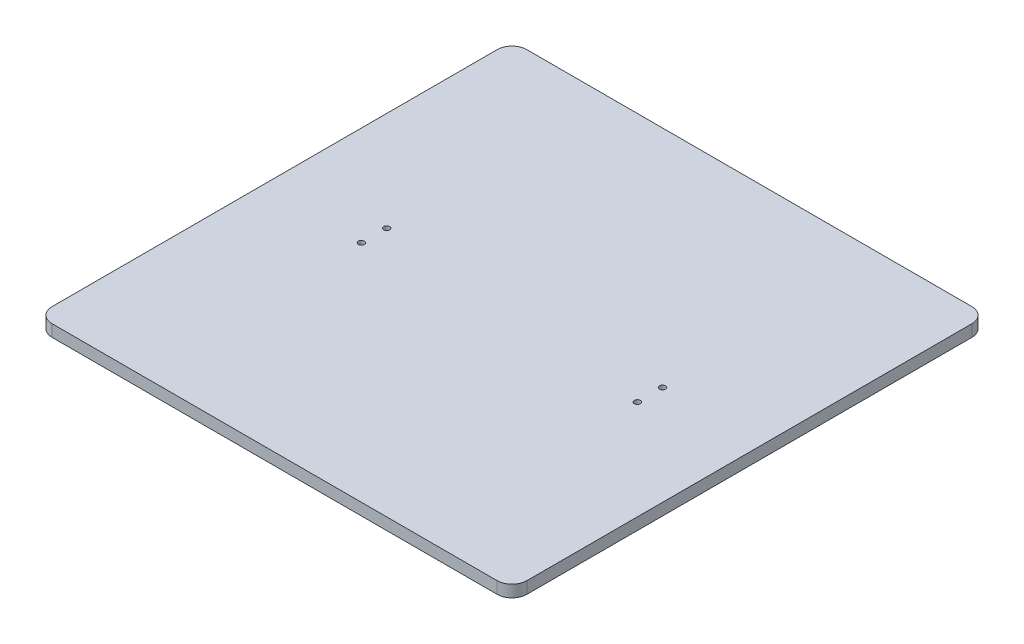
SolidWorks part; units mm, degrees
material "PMMA"
ref_plane "前视基准面" through (0, 0, 0) normal (0, 0, 1) x (1, 0, 0)
ref_plane "上视基准面" through (0, 0, 0) normal (0, 1, 0) x (1, 0, 0)
ref_plane "右视基准面" through (0, 0, 0) normal (1, 0, 0) x (0, 0, -1)
sketch "草图1" plane through (0, 0, 0) normal (0, 1, 0) x (1, 0, 0)
  line L1 (-150, -160) -> (150, -160)
  line L2 (-160, -150) -> (-160, 150)
  line L3 (-150, 160) -> (150, 160)
  line L4 (160, -150) -> (160, 150)
  line L5 (-160, -160) -> (160, 160) construction
  line L6 (-160, 160) -> (160, -160) construction
  arc A0 (160, -150) -> (150, -160) centre (150, -150) cw
  arc A1 (-150, -160) -> (-160, -150) centre (-150, -150) cw
  arc A2 (160, 150) -> (150, 160) centre (150, 150) ccw
  arc A3 (-150, 160) -> (-160, 150) centre (-150, 150) ccw
  point P0 (0, 0)
  dimension "D3" = 10
  dimension "D1" = 320
  dimension "D2" = 320
extrude "凸台-拉伸1" add sketch "草图1" against normal blind 8
sketch "草图2" plane through (0, -8, 0) normal (0, -1, 0) x (1, 0, 0)
  line L0 (-160, 0) -> (160, 0) construction
  line L1 (-160, -150) -> (-160, 150) construction
  line L2 (160, 150) -> (160, -150) construction
  line L3 (0, 160) -> (0, -160) construction
  line L4 (-150, 160) -> (150, 160) construction
  line L5 (150, -160) -> (-150, -160) construction
  circle A0 centre (-93, 8.5) radius 2
  circle A1 centre (93, 8.5) radius 2
  circle A2 centre (93, -8.5) radius 2
  circle A3 centre (-93, -8.5) radius 2
  dimension "D1" = 4
  dimension "D2" = 8.5
  dimension "D3" = 93
extrude "切除-拉伸1" cut sketch "草图2" against normal up to next
